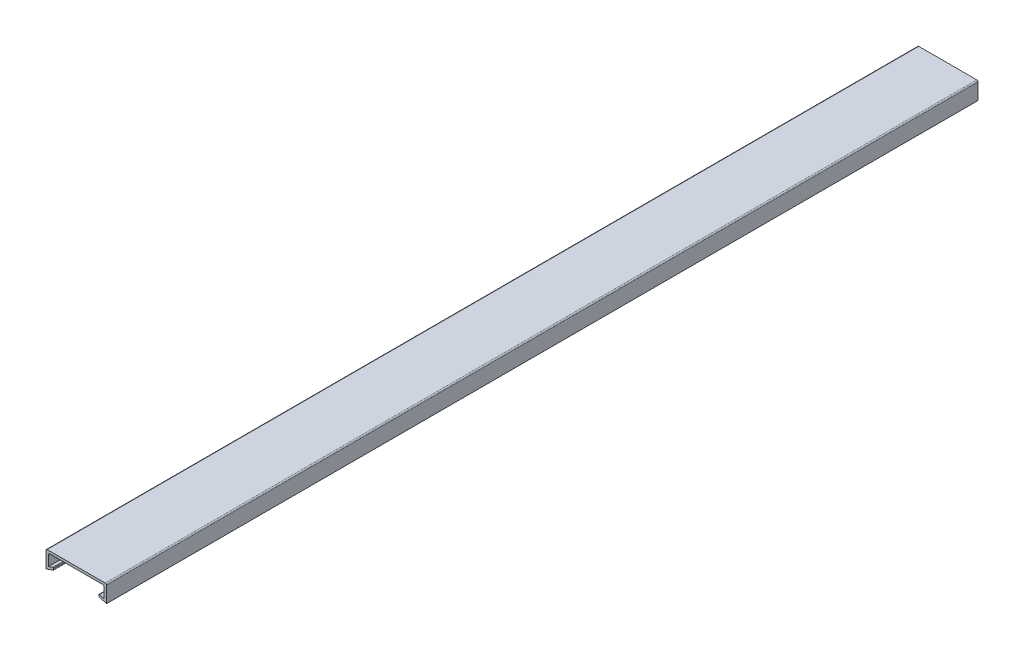
SolidWorks part; units mm, degrees
ref_plane "Alzado" through (0, 0, 0) normal (0, 0, 1) x (1, 0, 0)
ref_plane "Planta" through (0, 0, 0) normal (0, 1, 0) x (1, 0, 0)
ref_plane "Vista lateral" through (0, 0, 0) normal (1, 0, 0) x (0, 0, -1)
sketch "Croquis1" plane through (0, 0, 0) normal (0, 0, 1) x (1, 0, 0)
  line L0 (-9.3368, -6.0456) -> (-12.2, -7)
  line L1 (-12.2, -7) -> (-12.2, -0.5)
  line L2 (-11.7, 0) -> (11.7, 0)
  line L3 (12.2, -0.5) -> (12.2, -7)
  line L4 (0, 0) -> (0, -6.5) construction
  line L5 (9.2, -5.2775) -> (9.2, -5.8558)
  line L6 (9.3368, -6.0456) -> (12.2, -7)
  line L7 (11.2, -5.6667) -> (11.2, -1.5)
  line L8 (10.7, -1) -> (-10.7, -1)
  line L9 (-11.2, -1.5) -> (-11.2, -5.6667)
  line L10 (-11.2, -5.6667) -> (-9.4632, -5.0877)
  line L11 (-9.2, -5.2775) -> (-9.2, -5.8558)
  line L12 (11.2, -5.6667) -> (9.4632, -5.0877)
  arc A0 (11.7, 0) -> (12.2, -0.5) centre (11.7, -0.5) cw
  arc A1 (11.2, -1.5) -> (10.7, -1) centre (10.7, -1.5) ccw
  arc A2 (-10.7, -1) -> (-11.2, -1.5) centre (-10.7, -1.5) ccw
  arc A3 (-12.2, -0.5) -> (-11.7, 0) centre (-11.7, -0.5) cw
  arc A4 (9.2, -5.8558) -> (9.3368, -6.0456) centre (9.4, -5.8558) ccw
  arc A5 (9.2, -5.2775) -> (9.4632, -5.0877) centre (9.4, -5.2775) cw
  arc A6 (-9.3368, -6.0456) -> (-9.2, -5.8558) centre (-9.4, -5.8558) ccw
  arc A7 (-9.4632, -5.0877) -> (-9.2, -5.2775) centre (-9.4, -5.2775) cw
  point P13 (0, 0)
  point P19 (12.2, 0)
  point P26 (-12.2, 0)
  point P29 (9.2, -6)
  point P32 (9.2, -5)
  point P35 (-9.2, -6)
  point P38 (-9.2, -5)
  dimension "D9" = 0.5
  dimension "D10" = 0.2
  dimension "D2" = 1
  dimension "D3" = 1
  dimension "D4" = 1
  dimension "D5" = 24.4
  dimension "D6" = 3
  dimension "D7" = 2
  dimension "D8" = 1
  dimension "D11" = 7
extrude "Saliente-Extruir1" add sketch "Croquis1" along normal mid plane 352
